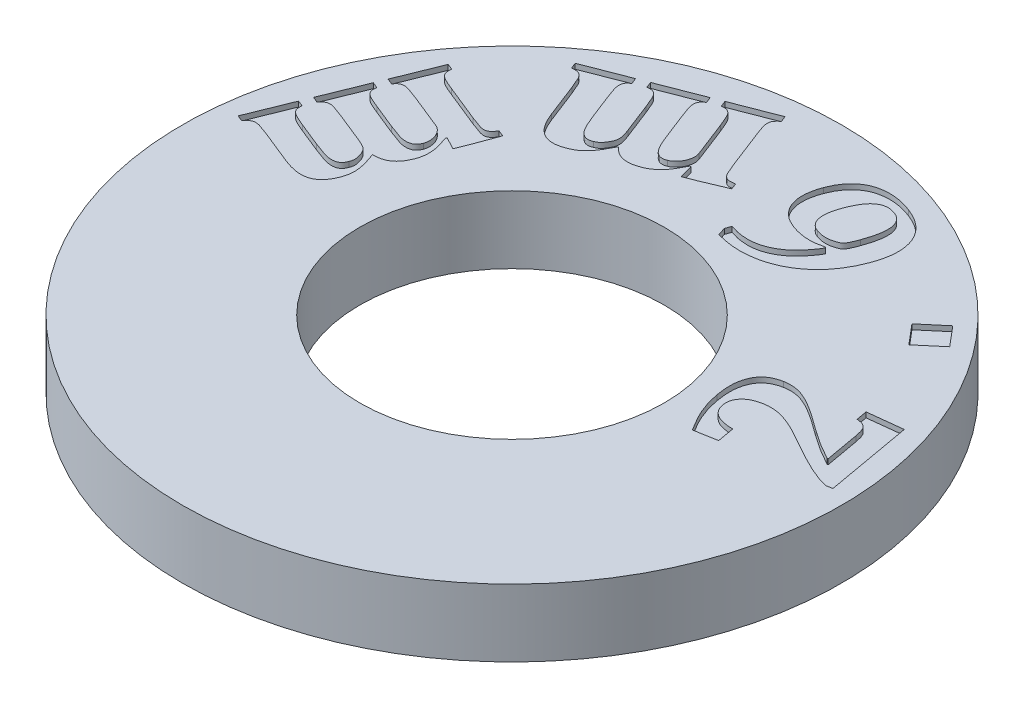
SolidWorks part; units mm, degrees
ref_plane "Front Plane" through (0, 0, 0) normal (0, 0, 1) x (1, 0, 0)
ref_plane "Top Plane" through (0, 0, 0) normal (0, 1, 0) x (1, 0, 0)
ref_plane "Right Plane" through (0, 0, 0) normal (1, 0, 0) x (0, 0, -1)
sketch "Sketch1" plane through (0, 0, 0) normal (0, 1, 0) x (1, 0, 0)
  circle A0 centre (0, 0) radius 12.7
  dimension "D1" = 25.4
extrude "Boss-Extrude1" add sketch "Sketch1" along normal blind 2.6
sketch "Sketch2" plane through (0, 0, 0) normal (0, -1, 0) x (-1, 0, 0)
  circle A0 centre (0, 0) radius 5.8674
  dimension "D1" = 11.7348
extrude "Cut-Extrude1" cut sketch "Sketch2" against normal through all
sketch "Sketch4" plane through (0, 2.6, 0) normal (0, 1, 0) x (1, 0, 0)
  circle A0 centre (0, 0) radius 12.0429 construction
  text T0 "<b>2.6mm</b>" font "Cambria" height 5.08
extrude "Cut-Extrude2" cut sketch "Sketch4" against normal blind 0.2
